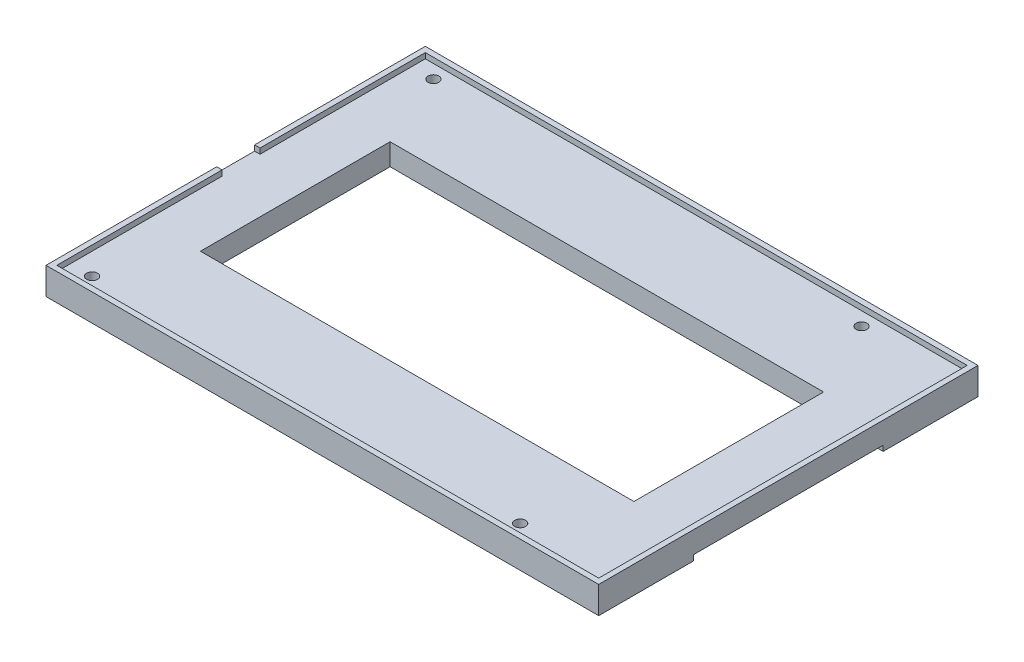
SolidWorks part; units mm, degrees
material "ПК/АБС"
ref_plane "Спереди" through (0, 0, 0) normal (0, 0, 1) x (1, 0, 0)
ref_plane "Сверху" through (0, 0, 0) normal (0, 1, 0) x (1, 0, 0)
ref_plane "Справа" through (0, 0, 0) normal (1, 0, 0) x (0, 0, -1)
sketch "Эскиз1" plane through (0, 0, 0) normal (0, 1, 0) x (1, 0, 0)
  line L1 (51, -35) -> (-51, -35)
  line L2 (51, -35) -> (51, 35)
  line L3 (51, 35) -> (-51, 35)
  line L4 (-51, -35) -> (-51, 35)
  line L5 (51, -35) -> (-51, 35) construction
  line L6 (51, 35) -> (-51, -35) construction
  point P0 (0, 0)
extrude "Бобышка-Вытянуть1" add sketch "Эскиз1" along normal blind 5
sketch "Эскиз2" plane through (0, 5, 0) normal (0, 1, 0) x (1, 0, 0)
  circle A0 centre (-46, 31.5) radius 1
  circle A1 centre (33, 31.5) radius 1
  circle A2 centre (33, -31.5) radius 1
  circle A3 centre (-46, -31.5) radius 1
extrude "Вырез-Вытянуть1" cut sketch "Эскиз2" against normal blind 4.5
sketch "Эскиз3" plane through (-51, 0, 0) normal (-1, 0, 0) x (0, 0, 1)
  line L3 (-35, 5) -> (35, 5) construction
  line L9 (-3.5, 5) -> (3.5, 5)
  line L10 (-3.5, 5) -> (-3.5, 4)
  line L11 (-3.5, 4) -> (3.5, 4)
  line L12 (3.5, 5) -> (3.5, 4)
extrude "Вырез-Вытянуть2" cut sketch "Эскиз3" against normal blind 2
sketch "Эскиз4" plane through (0, 0, 0) normal (0, -1, 0) x (1, 0, 0)
  line L11 (-40, 17.5) -> (40, 17.5)
  line L12 (-40, 17.5) -> (-40, -17.5)
  line L13 (-40, -17.5) -> (40, -17.5)
  line L14 (40, 17.5) -> (40, -17.5)
extrude "Вырез-Вытянуть3" cut sketch "Эскиз4" against normal blind 5
sketch "Эскиз5" plane through (0, 0, 0) normal (0, -1, 0) x (1, 0, 0)
  line L0 (51, 35) -> (51, -35) construction
  line L1 (40, 17.5) -> (51, 17.5)
  line L2 (40, 17.5) -> (40, -17.5)
  line L3 (40, -17.5) -> (51, -17.5)
  line L4 (51, 17.5) -> (51, -17.5)
extrude "Вырез-Вытянуть4" cut sketch "Эскиз5" against normal blind 1
sketch "Эскиз6" plane through (0, 5, 0) normal (0, 1, 0) x (1, 0, 0)
  line L7 (-50, 34) -> (50, 34)
  line L8 (-50, 34) -> (-50, -34)
  line L9 (-50, -34) -> (50, -34)
  line L10 (50, 34) -> (50, -34)
extrude "Вырез-Вытянуть5" cut sketch "Эскиз6" against normal blind 1
